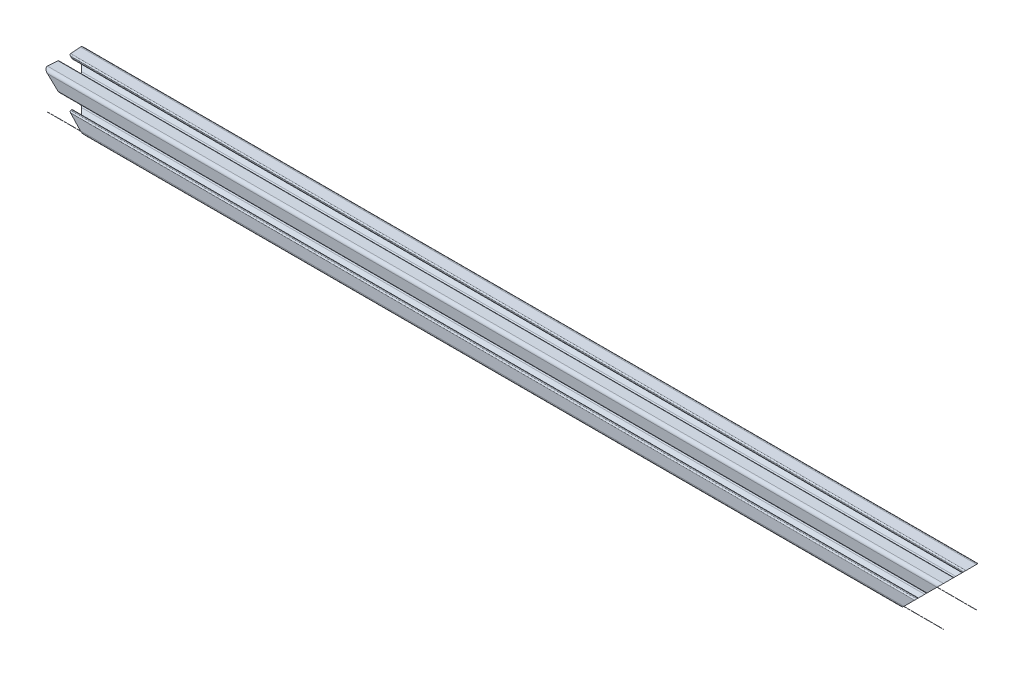
SolidWorks part; units mm, degrees
ref_plane "Front Plane" through (0, 0, 0) normal (0, 0, 1) x (1, 0, 0)
ref_plane "Top Plane" through (0, 0, 0) normal (0, 1, 0) x (1, 0, 0)
ref_plane "Right Plane" through (0, 0, 0) normal (1, 0, 0) x (0, 0, -1)
sketch "Sketch1" plane through (0, 0, 0) normal (1, 0, 0) x (0, 0, -1)
  line L0 (0, -12.7) -> (0, 12.7) construction
  line L1 (-7.874, 12.7) -> (7.874, 12.7) construction
  line L2 (-12.7, 0) -> (12.7, 0) construction
  line L3 (-7.874, 12.7) -> (-7.874, 4.826) construction
  line L4 (-3.302, 12.7) -> (3.302, 12.7) construction
  line L5 (-12.7, -12.7) -> (12.7, -12.7) construction
  line L6 (-12.7, 12.7) -> (12.7, 12.7) construction
  circle A0 centre (0, 0) radius 2.54 construction
  point P7 (0, 12.7)
  point P10 (0, 0)
  point P13 (0, 0)
  point P16 (0, 12.7)
  point P17 (-3.302, 12.7)
  point P18 (3.302, 12.7)
  point P21 (0, -12.7)
  point P24 (0, 12.7)
  dimension "Center Hole Diameter" = 5.08
  dimension "Rail Width" = 25.4
  dimension "Rail Height" = 25.4
  dimension "T-Slot Depth" = 7.874
  dimension "D1" = 15.748
  dimension "T-Slot Width" = 6.604
  dimension "D2" = 12.7
sketch "Sketch2" plane through (0, 0, 0) normal (0, 0, 1) x (1, 0, 0)
  line L0 (-287.3682, 0) -> (287.3682, 0) construction
  line L1 (0, 0) -> (0, 26.104) construction
  line L2 (287.3682, -12.7) -> (287.3682, 12.7) construction
  line L3 (-287.3682, -12.7) -> (-287.3682, 12.7) construction
  point P3 (-249.2682, 0)
  point P8 (0, 0)
  point P9 (249.2682, 0)
  point P12 (287.3682, 0)
  point P15 (-287.3682, 0)
  dimension "Length" = 574.7364
  dimension "D1" = 38.1
  dimension "D2" = 25.4
sketch "Sketch3" plane through (0, 0, 0) normal (1, 0, 0) x (0, 0, -1)
  line L0 (0, 4.826) -> (1.9842, 4.826)
  line L1 (0, -12.7) -> (0, 12.7) construction
  line L2 (4.2293, 5.7559) -> (7.5866, 9.1132)
  line L6 (7.0212, 10.4136) -> (4.0906, 10.3112)
  line L7 (3.302, 11.0728) -> (3.302, 11.7082)
  line L8 (-7.874, 12.7) -> (7.874, 12.7) construction
  line L10 (0, 0) -> (12.7, 12.7) construction
  line L13 (0, 4.826) -> (0, 2.54)
  line L14 (4.826, 0) -> (2.54, 0)
  line L31 (4.826, 0) -> (4.826, 1.9842)
  line L32 (4.0374, 12.4697) -> (10.5971, 12.6988)
  line L33 (-12.7, 0) -> (12.7, 0) construction
  line L34 (-12.7, 12.7) -> (12.7, 12.7) construction
  line L35 (5.7559, 4.2293) -> (9.1132, 7.5866)
  line L36 (0, 12.7) -> (12.7, 12.7) construction
  line L37 (12.7, 12.7) -> (12.7, 8.0234) construction
  line L38 (11.0728, 3.302) -> (11.7082, 3.302)
  line L39 (10.4136, 7.0212) -> (10.3112, 4.0906)
  line L40 (12.6988, 10.5971) -> (12.4697, 4.0374)
  arc A0 (2.54, 0) -> (0, 2.54) centre (0, 0) ccw
  arc A1 (1.9842, 4.826) -> (4.2293, 5.7559) centre (1.9842, 8.001) ccw
  circle A2 centre (0, 0) radius 2.54 construction
  arc A7 (3.302, 11.7082) -> (4.0374, 12.4697) centre (4.064, 11.7082) cw
  arc A8 (4.0906, 10.3112) -> (3.302, 11.0728) centre (4.064, 11.0728) cw
  arc A14 (4.826, 1.9842) -> (5.7559, 4.2293) centre (8.001, 1.9842) cw
  arc A16 (10.5971, 12.6988) -> (12.6988, 10.5971) centre (10.668, 10.668) cw
  arc A17 (7.0212, 10.4136) -> (7.5866, 9.1132) centre (7.0478, 9.652) cw
  arc A18 (10.4136, 7.0212) -> (9.1132, 7.5866) centre (9.652, 7.0478) ccw
  arc A19 (10.3112, 4.0906) -> (11.0728, 3.302) centre (11.0728, 4.064) ccw
  arc A20 (11.7082, 3.302) -> (12.4697, 4.0374) centre (11.7082, 4.064) ccw
  point P37 (3.2994, 4.826)
  point P49 (12.7, 3.302)
  point P52 (3.302, 12.7)
  point P55 (3.302, 10.2837)
  dimension "D4" = 3.175
  dimension "D9" = 2.159
  dimension "D12" = 0.762
  dimension "D3" = 2.032
  dimension "D8" = 0.762
  dimension "D2" = 45
  dimension "D5" = 2
  dimension "D6" = 45
  dimension "D7" = 2.159
extrude "Boss-Extrude1" add sketch "Sketch3" against normal up to vertex (287.3682 mm away) and the other way up to vertex (287.3682 mm away) up to point (-287.3682, 0, 0) other way up to point (287.3682, 0, 0)
mirror "Mirror1" about plane through (0, 0, 0) normal (0, 1, 0) of bodies 104
mirror "Mirror2" about plane through (0, 0, 0) normal (0, 0, 1) of bodies 105
sketch "Sketch4" plane through (-287.3682, 0, 0) normal (-1, 0, 0) x (0, 0, 1)
  line L0 (10.5971, 12.6988) -> (14.3503, 12.6988)
  line L1 (12.6988, 10.5971) -> (12.6988, 12.6988)
  line L2 (12.6988, 12.6988) -> (10.5971, 12.6988)
  line L3 (10.5971, -12.6988) -> (12.9087, -12.6988)
  line L4 (12.6988, -10.5971) -> (12.6988, -12.6988)
  line L5 (10.5971, 12.6988) -> (12.6988, 12.6988)
  line L6 (12.6988, -12.6988) -> (12.6988, 12.6988)
ref_plane "Plane2" through (0, 0, 12.6988) normal (0, 0, -1) x (-1, 0, 0)
sketch "Sketch6" plane through (0, 0, 12.6988) normal (0, 0, -1) x (-1, 0, 0)
  line L0 (287.3682, -12.6988) -> (261.9682, -12.6988)
  line L1 (287.3682, 12.6988) -> (261.9682, -12.6988)
  dimension "D1" = 25.4
extrude "Cut-Extrude5" cut sketch "Sketch6" against normal through all and the other way through all
ref_plane "Plane3" through (-137.3207, -137.3341, 0) normal (-0.7071, -0.7071, 0) x (-0.7071, 0.7071, 0)
sketch "Sketch9" plane through (0, -12.6988, 0) normal (0, 1, 0) x (1, 0, 0)
  line L0 (-261.9682, -10.5971) -> (-261.9682, -10.7389)
sketch "Sketch10" plane through (287.3682, 0, 0) normal (1, 0, 0) x (0, 0, -1)
  line L0 (10.5971, 12.6988) -> (13.6109, 12.6988)
  line L1 (12.6988, 10.5971) -> (12.6988, 12.6988)
  line L2 (10.5971, -12.6988) -> (13.9193, -12.6988)
  line L3 (12.6988, -10.5971) -> (12.6988, -12.6988)
ref_plane "Plane4" through (0, 0, -12.6988) normal (0, 0, -1) x (-1, 0, 0)
sketch "Sketch12" plane through (0, 0, -12.6988) normal (0, 0, -1) x (-1, 0, 0)
  line L0 (-287.3682, -12.6988) -> (-261.9682, -12.6988)
  line L1 (-261.9682, -12.6988) -> (-287.3682, 12.6988)
  dimension "D1" = 25.4
extrude "Cut-Extrude8" cut sketch "Sketch12" against normal through all and the other way through all
equation "\"D1@Sketch2\"=\"Rail Height@Sketch1\"*1.5"
equation "\"D2@Sketch2\"=\"Rail Height@Sketch1\""
